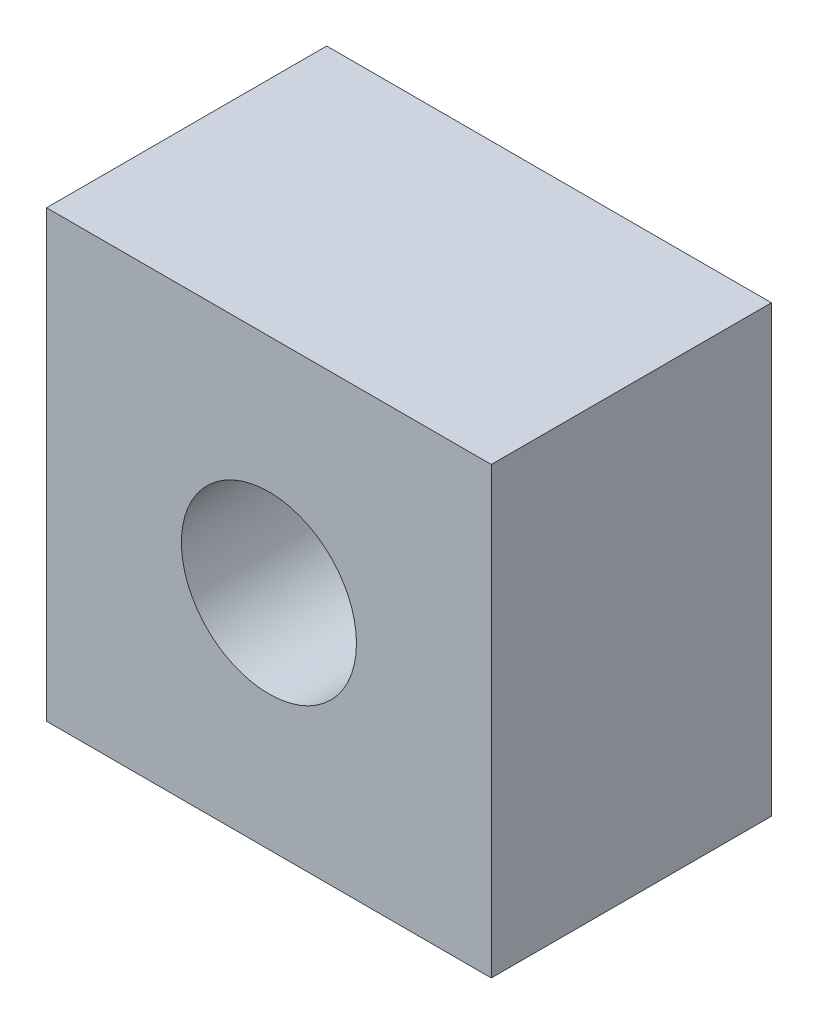
SolidWorks part; units mm, degrees
ref_plane "正面" through (0, 0, 0) normal (0, 0, 1) x (1, 0, 0)
ref_plane "平面" through (0, 0, 0) normal (0, 1, 0) x (1, 0, 0)
ref_plane "右側面" through (0, 0, 0) normal (1, 0, 0) x (0, 0, -1)
sketch "ｽｹｯﾁ1" plane through (0, 0, 0) normal (0, 0, 1) x (1, 0, 0)
  line L1 (-1.27, 1.27) -> (1.27, 1.27)
  line L2 (-1.27, 1.27) -> (-1.27, -1.27)
  line L3 (-1.27, -1.27) -> (1.27, -1.27)
  line L4 (1.27, 1.27) -> (1.27, -1.27)
  line L5 (-1.27, 1.27) -> (1.27, -1.27) construction
  line L6 (-1.27, -1.27) -> (1.27, 1.27) construction
  point P0 (0, 0)
  dimension "D1" = 2.54
extrude "ﾎﾞｽ - 押し出し1" add sketch "ｽｹｯﾁ1" along normal blind 1.6
sketch "ｽｹｯﾁ2" plane through (0, 0, 1.6) normal (0, 0, 1) x (1, 0, 0)
  circle A0 centre (0, 0) radius 0.5
  dimension "D1" = 1
extrude "ｶｯﾄ - 押し出し1" cut sketch "ｽｹｯﾁ2" against normal through all
